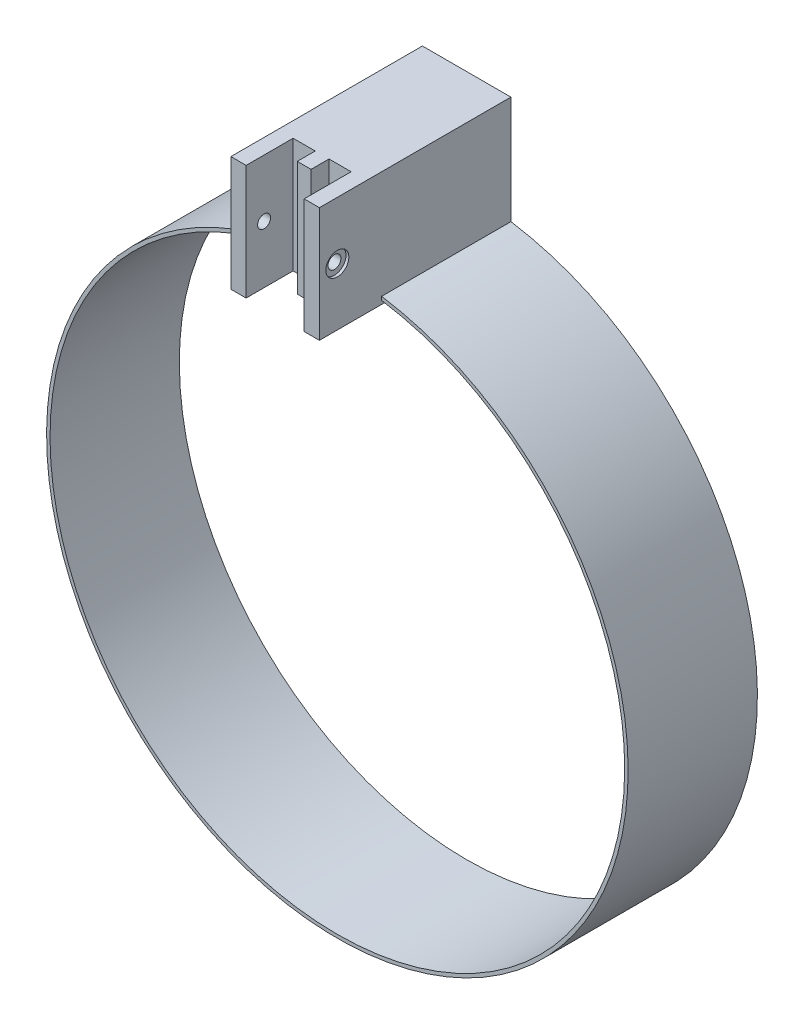
SolidWorks part; units mm, degrees
ref_plane "Plan de face" through (0, 0, 0) normal (0, 0, 1) x (1, 0, 0)
ref_plane "Plan de dessus" through (0, 0, 0) normal (0, 1, 0) x (1, 0, 0)
ref_plane "Plan de droite" through (0, 0, 0) normal (1, 0, 0) x (0, 0, -1)
sketch "Base" plane through (0, 0, 0) normal (0, 1, 0) x (1, 0, 0)
  line L0 (-3.85, -2.4) -> (-3.85, 2.4)
  line L1 (-3.85, 2.4) -> (-10.1, 2.4)
  line L2 (-10.1, 2.4) -> (-10.1, 10.1)
  line L3 (-10.1, 10.1) -> (-2.4, 10.1)
  line L4 (-2.4, 10.1) -> (-2.4, 3.85)
  line L5 (-2.4, 3.85) -> (2.4, 3.85)
  line L6 (0, -55) -> (0, 55) construction
  line L7 (2.4, 10.1) -> (2.4, 3.85)
  line L8 (10.1, 10.1) -> (2.4, 10.1)
  line L9 (10.1, 2.4) -> (10.1, 10.1)
  line L10 (3.85, 2.4) -> (10.1, 2.4)
  line L11 (3.85, -2.4) -> (3.85, 2.4)
  line L12 (-55, 0) -> (55, 0) construction
  line L13 (3.85, -2.4) -> (10.1, -2.4)
  line L14 (10.1, -2.4) -> (10.1, -6.25)
  line L20 (-10.1, -2.4) -> (-10.1, -6.25)
  line L21 (-3.85, -2.4) -> (-10.1, -2.4)
  line L23 (-15.4, 15.4) -> (15.4, 15.4)
  line L24 (-15.4, 15.4) -> (-15.4, -6.25)
  line L26 (15.4, 15.4) -> (15.4, -6.25)
  line L27 (-15.4, 15.4) -> (0, 0) construction
  line L28 (0, 0) -> (15.4, 15.4) construction
  line L29 (-10.1, -6.25) -> (-15.4, -6.25)
  line L30 (10.1, -6.25) -> (15.4, -6.25)
  line L31 (10.1, -10.1) -> (15.4, -15.4) construction
  point P2 (-3.85, 0)
  point P3 (0, 3.85)
  point P27 (0, 0)
  dimension "D1" = 4.8
  dimension "D2" = 4.8
  dimension "D3" = 6.25
  dimension "D4" = 7.7
  dimension "D5" = 30.8
extrude "Boss.-Extru.1" add sketch "Base" along normal mid plane 40
hole_wizard "Chambrage pour vis à six pans creux M41" positions "Esquisse4" profile "Esquisse5" counterbore size "M4" standard "ISO"
sketch "Esquisse4" plane through (15.4, 0, 0) normal (1, 0, 0) x (0, 0, -1)
  point P0 (0, 0)
sketch "Esquisse5" plane through (15.4, 0, 0) normal (0, 1, 0) x (0, 0, -1)
  line L0 (0, 0) -> (0, 11.55)
  line L1 (0, 11.55) -> (2.25, 11.55)
  line L3 (2.25, 11.55) -> (2.25, 1)
  line L4 (2.25, 1) -> (4, 1)
  line L5 (4, 1) -> (4, 0)
  line L7 (4, 0) -> (0, 0)
  line L11 (0, -6.35) -> (0, 107.95) construction
  dimension "Diamètre du perçage jusqu'au prochain" = 4.5
  dimension "Profondeur du perçage jusqu'au prochain" = 11.55
  dimension "Diamètre du chambrage" = 8
  dimension "Profondeur du chambrage" = 1
mirror "Symétrie1" about plane through (0, 0, 0) normal (1, 0, 0) of "Chambrage pour vis à six pans creux M41"
sketch "Esquisse6" plane through (0, 0, 0) normal (0, 0, 1) x (1, 0, 0)
  line L0 (10.1, 20) -> (10.1, -20) construction
  line L1 (-10.1, 20) -> (10.1, 20)
  line L2 (-10.1, 20) -> (-10.1, -20)
  line L3 (-10.1, -20) -> (10.1, -20)
  line L4 (10.1, 20) -> (10.1, -20)
  line L5 (-10.1, 20) -> (10.1, -20) construction
  line L6 (-10.1, -20) -> (10.1, 20) construction
  line L7 (-10.1, 20) -> (-3.85, 20) construction
  point P0 (0, 0)
  point P8 (-10.1, 20)
extrude "Enlèv. mat.-Extru.1" cut sketch "Esquisse6" against normal mid plane 6
sketch "Esquisse16" plane through (0, 0, -15.4) normal (0, 0, -1) x (-1, 0, 0)
  circle A0 centre (0, -117.5665) radius 100
  point P0 (0, -117.5665)
extrude "Extru.-Mince1" add sketch "Esquisse16" along normal blind 45 thin
sketch "Esquisse14" plane through (0, -20, 0) normal (0, -1, 0) x (1, 0, 0)
  line L0 (15.4, 6.25) -> (15.4, -15.4) construction
  line L1 (-15.4, -15.4) -> (15.4, -15.4)
  line L2 (-15.4, -15.4) -> (-15.4, -60.4)
  line L3 (-15.4, -60.4) -> (15.4, -60.4)
  line L4 (15.4, -15.4) -> (15.4, -60.4)
  dimension "D1" = 45
extrude "Boss.-Extru.3" add sketch "Esquisse14" against normal up to vertex (40 mm away)
